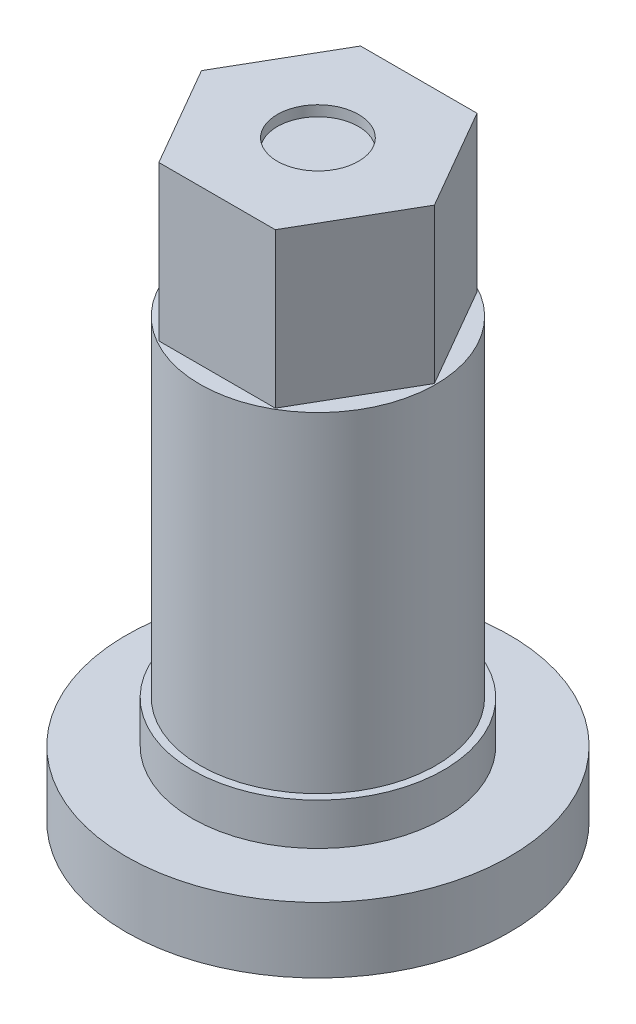
SolidWorks part; units mm, degrees
material "ABS"
ref_plane "Front Plane" through (0, 0, 0) normal (0, 0, 1) x (1, 0, 0)
ref_plane "Top Plane" through (0, 0, 0) normal (0, 1, 0) x (1, 0, 0)
ref_plane "Right Plane" through (0, 0, 0) normal (1, 0, 0) x (0, 0, -1)
sketch "Sketch1" plane through (0, 0, 0) normal (0, 1, 0) x (1, 0, 0)
  circle A0 centre (0, 0) radius 3.66
  dimension "D1" = 7.32
extrude "Boss-Extrude1" add sketch "Sketch1" along normal blind 1.25 contours A0
sketch "Sketch2" plane through (0, 1.25, 0) normal (0, 1, 0) x (1, 0, 0)
  circle A0 centre (0, 0) radius 2.4
  dimension "D1" = 4.8
extrude "Boss-Extrude2" add sketch "Sketch2" along normal blind 0.8
sketch "Sketch3" plane through (0, 2.05, 0) normal (0, 1, 0) x (1, 0, 0)
  circle A0 centre (0, 0) radius 2.25
  dimension "D1" = 4.5
extrude "Boss-Extrude3" add sketch "Sketch3" along normal blind 6.3
sketch "Sketch4" plane through (0, 8.35, 0) normal (0, 1, 0) x (1, 0, 0)
  line L1 (-2.2228, 0) -> (-1.1114, -1.925)
  line L2 (-1.1114, -1.925) -> (1.1114, -1.925)
  line L3 (1.1114, -1.925) -> (2.2228, 0)
  line L4 (2.2228, 0) -> (1.1114, 1.925)
  line L5 (1.1114, 1.925) -> (-1.1114, 1.925)
  line L6 (-1.1114, 1.925) -> (-2.2228, 0)
  circle A0 centre (0, 0) radius 1.925 construction
extrude "Boss-Extrude4" add sketch "Sketch4" along normal blind 2.95
sketch "Sketch5" plane through (0, 11.3, 0) normal (0, 1, 0) x (1, 0, 0)
  circle A0 centre (0, 0) radius 0.775
  dimension "D1" = 1.55
extrude "Cut-Extrude4" cut sketch "Sketch5" against normal blind 0.2
sketch "Sketch7" plane through (0, 0, 0) normal (0, -1, 0) x (1, 0, 0)
  line L1 (-0.95, 0) -> (-0.475, -0.8227)
  line L2 (-0.475, -0.8227) -> (0.475, -0.8227)
  line L3 (0.475, -0.8227) -> (0.95, 0)
  line L4 (0.95, 0) -> (0.475, 0.8227)
  line L5 (0.475, 0.8227) -> (-0.475, 0.8227)
  line L6 (-0.475, 0.8227) -> (-0.95, 0)
  circle A0 centre (0, 0) radius 0.95 construction
extrude "Cut-Extrude7" cut sketch "Sketch7" against normal blind 10.77
